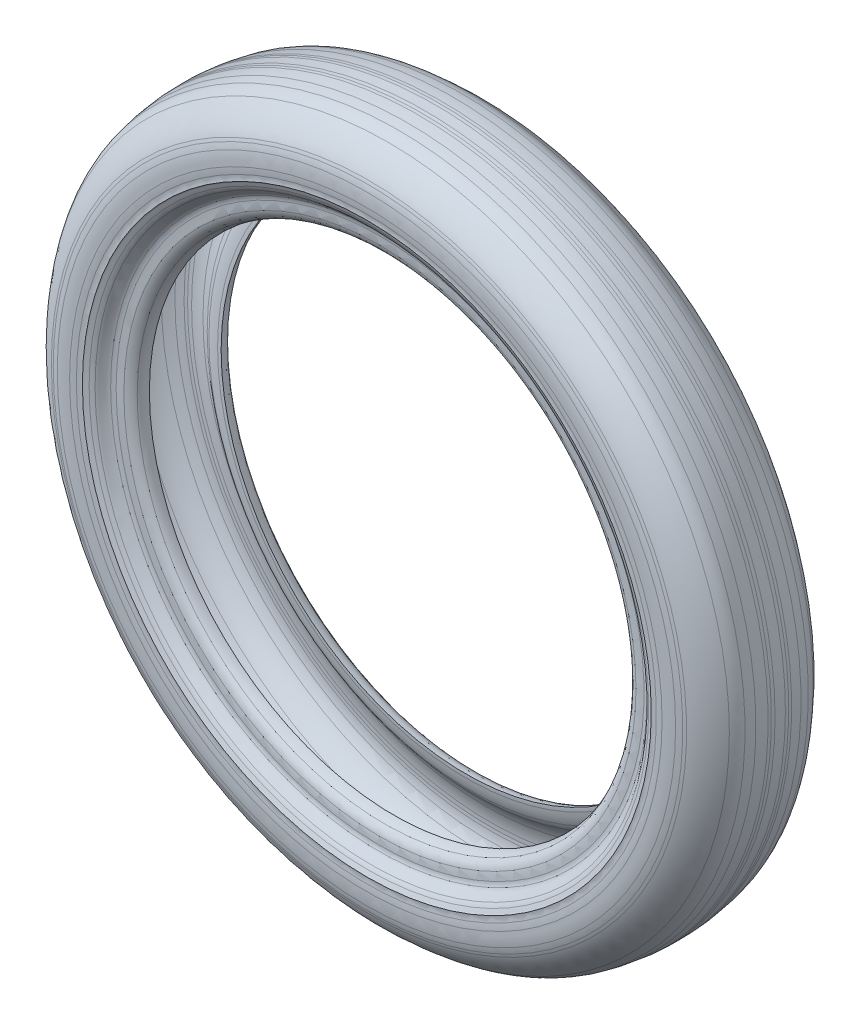
SolidWorks part; units mm, degrees
material "BUTYL"
ref_plane "Front" through (0, 0, 0) normal (0, 0, 1) x (1, 0, 0)
ref_plane "Top" through (0, 0, 0) normal (0, 1, 0) x (1, 0, 0)
ref_plane "Right" through (0, 0, 0) normal (1, 0, 0) x (0, 0, -1)
ref_axis "Centre Axis" through (0, 0, -80.9) along (0, 0, 1)
sketch "Sketch1" plane through (0, 0, 0) normal (1, 0, 0) x (0, 0, -1)
  line L0 (0, 50) -> (0, -50) construction
  line L1 (0, -33.8436) -> (0, -9.9037) construction
  line L2 (-4.0872, 277) -> (4.0872, 277)
  line L4 (-203.2338, 0) -> (-81.6295, 0) construction
  line L5 (80.9, 0) -> (-80.9, 0) construction
  spline S0 degree 3 poles (1.6419, 271.653) (1.1029, 271.6532) (0.5529, 271.6571) (0, 271.6602) knots 0 0 0 0 0.347073 0.347073 0.347073 0.347073
  spline S1 degree 3 poles (6.3798, 271.5034) (4.7592, 271.5225) (3.311, 271.6526) (1.6419, 271.653) knots 0 0 0 0 1 1 1 1
  spline S2 degree 3 poles (10.3535, 271.2068) (8.9789, 271.4256) (7.7759, 271.4869) (6.3798, 271.5034) knots 0 0 0 0 1 1 1 1
  spline S3 degree 3 poles (12.7989, 270.9054) (11.9638, 270.9691) (11.1939, 271.073) (10.3535, 271.2068) knots 0 0 0 0 1 1 1 1
  spline S4 degree 3 poles (15.5499, 270.5943) (14.6039, 270.7389) (13.7382, 270.8335) (12.7989, 270.9054) knots 0 0 0 0 1 1 1 1
  spline S5 degree 3 poles (21.6633, 269.1036) (19.632, 269.9162) (17.6947, 270.2662) (15.5499, 270.5943) knots 0 0 0 0 1 1 1 1
  spline S6 degree 3 poles (28.9995, 266.6957) (26.5833, 267.7421) (24.0838, 268.1352) (21.6633, 269.1036) knots 0 0 0 0 1 1 1 1
  spline S7 degree 3 poles (42.4035, 255.1468) (39.1962, 260.1434) (34.4609, 264.3299) (28.9995, 266.6957) knots 0 0 0 0 1 1 1 1
  spline S8 degree 3 poles (46.2013, 248.1154) (45.5039, 250.3511) (43.6949, 253.1348) (42.4035, 255.1468) knots 0 0 0 0 1 1 1 1
  spline S9 degree 3 poles (47.3486, 242.0029) (47.1655, 243.943) (46.7705, 246.2905) (46.2013, 248.1154) knots 0 0 0 0 1 1 1 1
  spline S10 degree 3 poles (47.4951, 239.4047) (47.5171, 240.3133) (47.4328, 241.1112) (47.3486, 242.0029) knots 0 0 0 0 1 1 1 1
  spline S11 degree 3 poles (-28.3847, 193.735) (-30.8155, 193.9745) (-33.7279, 194.5547) (-35.7019, 196.0514) knots 0.040131 0.040131 0.040131 0.040131 1 1 1 1
  spline S12 degree 3 poles (-35.7019, 196.0514) (-37.692, 197.5602) (-39.1936, 200.1049) (-39.6882, 202.5712) knots 0 0 0 0 1 1 1 1
  spline S13 degree 3 poles (-39.6882, 202.5712) (-40.0688, 204.4684) (-39.4456, 206.8864) (-39.5739, 208.8375) knots 0 0 0 0 1 1 1 1
  spline S14 degree 3 poles (-39.5739, 208.8375) (-39.6532, 210.0457) (-40.035, 211.0863) (-40.5539, 212.1996) knots 0 0 0 0 1 1 1 1
  spline S15 degree 3 poles (-40.5539, 212.1996) (-41.8913, 215.0694) (-44.8441, 216.1154) (-46.708, 218.3615) knots 0 0 0 0 1 1 1 1
  spline S16 degree 3 poles (-46.708, 218.3615) (-47.4706, 219.2805) (-47.9073, 220.3199) (-48.4225, 221.37) knots 0 0 0 0 1 1 1 1
  spline S17 degree 3 poles (-48.4225, 221.37) (-49.0979, 222.7469) (-49.2527, 223.872) (-50.0908, 225.0381) knots 0 0 0 0 1 1 1 1
  spline S18 degree 3 poles (-50.0908, 225.0381) (-49.8241, 226.5489) (-50.1827, 227.7673) (-50.4121, 229.4703) knots 0 0 0 0 1 1 1 1
  spline S19 degree 3 poles (-50.4121, 229.4703) (-50.6535, 231.2622) (-50.8326, 232.5706) (-50.8519, 234.3611) knots 0 0 0 0 1 1 1 1
  spline S20 degree 3 poles (-50.8519, 234.3611) (-50.8887, 237.7826) (-50.9986, 241.2677) (-50.3807, 244.6011) knots 0 0 0 0 1 1 1 1
  spline S21 degree 3 poles (-50.3807, 244.6011) (-50.1017, 246.1062) (-49.614, 247.5731) (-49.1525, 249.0333) knots 0 0 0 0 1 1 1 1
  spline S22 degree 3 poles (-49.1525, 249.0333) (-48.9054, 249.8149) (-48.6779, 250.5651) (-48.3688, 251.3259) knots 0 0 0 0 1 1 1 1
  spline S23 degree 3 poles (-48.3688, 251.3259) (-45.4098, 258.6096) (-39.3425, 265.1512) (-33.126, 269.8722) knots 0 0 0 0 1 1 1 1
  spline S24 degree 3 poles (-33.126, 269.8722) (-30.6554, 271.7484) (-28.0416, 273.3908) (-25.0257, 274.1647) knots 0 0 0 0 1 1 1 1
  spline S25 degree 3 poles (-25.0257, 274.1647) (-22.6554, 274.773) (-20.2681, 275.2075) (-17.8425, 275.5855) knots 0 0 0 0 1 1 1 1
  spline S26 degree 3 poles (-17.8425, 275.5855) (-15.0109, 276.0267) (-12.1293, 276.5109) (-9.2836, 276.7114) knots 0 0 0 0 1 1 1 1
  spline S27 degree 3 poles (-9.2836, 276.7114) (-8.4473, 276.7704) (-7.6883, 276.821) (-6.8383, 276.8704) knots 0 0 0 0 1 1 1 1
  spline S28 degree 3 poles (-6.8383, 276.8704) (-5.8867, 276.9257) (-5.0354, 276.993) (-4.0872, 277) knots 0 0 0 0 1 1 1 1
  spline S29 degree 3 poles (47.3071, 236.0423) (47.3951, 237.206) (47.467, 238.2419) (47.4951, 239.4047) knots 0 0 0 0 1 1 1 1
  spline S30 degree 3 poles (43.5008, 223.2041) (45.4348, 227.1932) (46.9739, 231.6345) (47.3071, 236.0423) knots 0 0 0 0 1 1 1 1
  spline S31 degree 3 poles (35.6066, 211.9645) (38.5739, 215.4752) (41.488, 219.0521) (43.5008, 223.2041) knots 0 0 0 0 1 1 1 1
  spline S32 degree 3 poles (31.8567, 206.8506) (32.81, 208.7628) (34.2411, 210.3489) (35.6066, 211.9645) knots 0 0 0 0 1 1 1 1
  spline S33 degree 3 poles (28.7716, 196.9163) (29.3926, 200.2802) (30.3239, 203.7766) (31.8567, 206.8506) knots 0 0 0 0 1 1 1 1
  spline S34 degree 3 poles (28.3847, 193.735) (28.411, 194.8748) (28.569, 195.8192) (28.7716, 196.9163) knots -0.038042 -0.038042 -0.038042 -0.038042 1 1 1 1
  spline S35 degree 3 poles (6.8383, 276.8704) (5.8867, 276.9257) (5.0354, 276.993) (4.0872, 277) knots 0 0 0 0 1 1 1 1
  spline S36 degree 3 poles (9.2836, 276.7114) (8.4473, 276.7704) (7.6883, 276.821) (6.8383, 276.8704) knots 0 0 0 0 1 1 1 1
  spline S37 degree 3 poles (17.8425, 275.5855) (15.0109, 276.0267) (12.1293, 276.5109) (9.2836, 276.7114) knots 0 0 0 0 1 1 1 1
  spline S38 degree 3 poles (25.0257, 274.1647) (22.6554, 274.773) (20.2681, 275.2075) (17.8425, 275.5855) knots 0 0 0 0 1 1 1 1
  spline S39 degree 3 poles (33.126, 269.8722) (30.6554, 271.7484) (28.0416, 273.3908) (25.0257, 274.1647) knots 0 0 0 0 1 1 1 1
  spline S40 degree 3 poles (48.3688, 251.3259) (45.4098, 258.6096) (39.3425, 265.1512) (33.126, 269.8722) knots 0 0 0 0 1 1 1 1
  spline S41 degree 3 poles (-28.3847, 193.735) (-28.411, 194.8748) (-28.569, 195.8192) (-28.7716, 196.9163) knots -0.038042 -0.038042 -0.038042 -0.038042 1 1 1 1
  spline S42 degree 3 poles (-28.7716, 196.9163) (-29.3926, 200.2802) (-30.3239, 203.7766) (-31.8567, 206.8506) knots 0 0 0 0 1 1 1 1
  spline S43 degree 3 poles (-31.8567, 206.8506) (-32.81, 208.7628) (-34.2411, 210.3489) (-35.6066, 211.9645) knots 0 0 0 0 1 1 1 1
  spline S44 degree 3 poles (-35.6066, 211.9645) (-38.5739, 215.4752) (-41.488, 219.0521) (-43.5008, 223.2041) knots 0 0 0 0 1 1 1 1
  spline S45 degree 3 poles (-43.5008, 223.2041) (-45.4348, 227.1932) (-46.9739, 231.6345) (-47.3071, 236.0423) knots 0 0 0 0 1 1 1 1
  spline S46 degree 3 poles (-47.3071, 236.0423) (-47.3951, 237.206) (-47.467, 238.2419) (-47.4951, 239.4047) knots 0 0 0 0 1 1 1 1
  spline S47 degree 3 poles (-47.4951, 239.4047) (-47.5171, 240.3133) (-47.4328, 241.1112) (-47.3486, 242.0029) knots 0 0 0 0 1 1 1 1
  spline S48 degree 3 poles (-47.3486, 242.0029) (-47.1655, 243.943) (-46.7705, 246.2905) (-46.2013, 248.1154) knots 0 0 0 0 1 1 1 1
  spline S49 degree 3 poles (-46.2013, 248.1154) (-45.5039, 250.3511) (-43.6949, 253.1348) (-42.4035, 255.1468) knots 0 0 0 0 1 1 1 1
  spline S50 degree 3 poles (-42.4035, 255.1468) (-39.1962, 260.1434) (-34.4609, 264.3299) (-28.9995, 266.6957) knots 0 0 0 0 1 1 1 1
  spline S51 degree 3 poles (-28.9995, 266.6957) (-26.5833, 267.7421) (-24.0838, 268.1352) (-21.6633, 269.1036) knots 0 0 0 0 1 1 1 1
  spline S52 degree 3 poles (-21.6633, 269.1036) (-19.632, 269.9162) (-17.6947, 270.2662) (-15.5499, 270.5943) knots 0 0 0 0 1 1 1 1
  spline S53 degree 3 poles (-15.5499, 270.5943) (-14.6039, 270.7389) (-13.7382, 270.8335) (-12.7989, 270.9054) knots 0 0 0 0 1 1 1 1
  spline S54 degree 3 poles (-12.7989, 270.9054) (-11.9638, 270.9691) (-11.1939, 271.073) (-10.3535, 271.2068) knots 0 0 0 0 1 1 1 1
  spline S55 degree 3 poles (-10.3535, 271.2068) (-8.9789, 271.4256) (-7.7759, 271.4869) (-6.3798, 271.5034) knots 0 0 0 0 1 1 1 1
  spline S56 degree 3 poles (-6.3798, 271.5034) (-4.7592, 271.5225) (-3.311, 271.6526) (-1.6419, 271.653) knots 0 0 0 0 1 1 1 1
  spline S57 degree 3 poles (-1.6419, 271.653) (-1.1029, 271.6532) (-0.5529, 271.6571) (0, 271.6602) knots 0 0 0 0 0.347073 0.347073 0.347073 0.347073
  spline S58 degree 3 poles (49.1525, 249.0333) (48.9054, 249.8149) (48.6779, 250.5651) (48.3688, 251.3259) knots 0 0 0 0 1 1 1 1
  spline S59 degree 3 poles (50.3807, 244.6011) (50.1017, 246.1062) (49.614, 247.5731) (49.1525, 249.0333) knots 0 0 0 0 1 1 1 1
  spline S60 degree 3 poles (50.8519, 234.3611) (50.8887, 237.7826) (50.9986, 241.2677) (50.3807, 244.6011) knots 0 0 0 0 1 1 1 1
  spline S61 degree 3 poles (50.4121, 229.4703) (50.6535, 231.2622) (50.8326, 232.5706) (50.8519, 234.3611) knots 0 0 0 0 1 1 1 1
  spline S62 degree 3 poles (50.0908, 225.0381) (49.8241, 226.5489) (50.1827, 227.7673) (50.4121, 229.4703) knots 0 0 0 0 1 1 1 1
  spline S63 degree 3 poles (48.4225, 221.37) (49.0979, 222.7469) (49.2527, 223.872) (50.0908, 225.0381) knots 0 0 0 0 1 1 1 1
  spline S64 degree 3 poles (46.708, 218.3615) (47.4706, 219.2805) (47.9073, 220.3199) (48.4225, 221.37) knots 0 0 0 0 1 1 1 1
  spline S65 degree 3 poles (40.5539, 212.1996) (41.8913, 215.0694) (44.8441, 216.1154) (46.708, 218.3615) knots 0 0 0 0 1 1 1 1
  spline S66 degree 3 poles (39.5739, 208.8375) (39.6532, 210.0457) (40.035, 211.0863) (40.5539, 212.1996) knots 0 0 0 0 1 1 1 1
  spline S67 degree 3 poles (39.6882, 202.5712) (40.0688, 204.4684) (39.4456, 206.8864) (39.5739, 208.8375) knots 0 0 0 0 1 1 1 1
  spline S68 degree 3 poles (35.7019, 196.0514) (37.692, 197.5602) (39.1936, 200.1049) (39.6882, 202.5712) knots 0 0 0 0 1 1 1 1
  spline S69 degree 3 poles (28.3847, 193.735) (30.8155, 193.9745) (33.7279, 194.5547) (35.7019, 196.0514) knots 0.040131 0.040131 0.040131 0.040131 1 1 1 1
  dimension "D1" = 101.7037
  dimension "D2" = 554
  dimension "D3" = 56.7694
  dimension "D4" = 387.4701
  dimension "D5" = 79.3764
  dimension "D6" = 417.675
revolve "Revolve1" add sketch "Sketch1" angle 360 about axis through (0, 0, -80.9) along (0, 0, 1)
